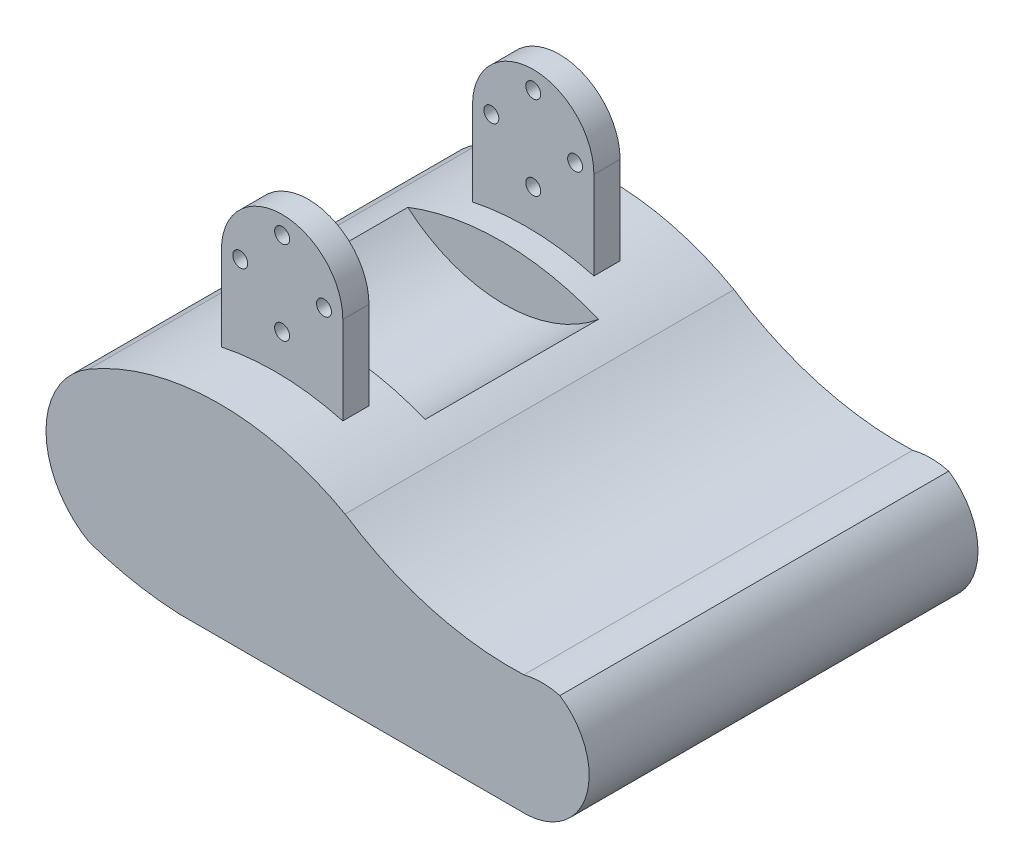
SolidWorks part; units mm, degrees
material "PLA"
ref_plane "Front Plane" through (0, 0, 0) normal (0, 0, 1) x (1, 0, 0)
ref_plane "Top Plane" through (0, 0, 0) normal (0, 1, 0) x (1, 0, 0)
ref_plane "Right Plane" through (0, 0, 0) normal (1, 0, 0) x (0, 0, -1)
sketch "Sketch1" plane through (0, 0, 0) normal (0, 0, 1) x (1, 0, 0)
  line L0 (-30, 0) -> (50, 0)
  line L1 (0, 0) -> (0, 25) construction
  line L2 (-30, 0) -> (-30, 25) construction
  line L3 (50, 0) -> (34.8329, 0) construction
  line L4 (-15, -2.8863) -> (48.734, -2.8863) construction
  line L5 (48.734, -2.8863) -> (48.734, 17.1137) construction
  line L6 (-15, -2.8863) -> (42.0254, -2.8863)
  line L7 (48.734, 17.1137) -> (42.7081, 17.1137) construction
  line L8 (-37.1668, 12.5) -> (-7.1668, 12.5) construction
  line L9 (-7.1668, 12.5) -> (12.8332, 12.5) construction
  line L10 (12.8332, 12.5) -> (12.8332, 25.4411) construction
  arc A0 (-30, 25) -> (-30, 0) centre (-22.6825, 12.5) ccw
  arc A7 (-30, 0) -> (-15, -2.8863) centre (-12.2067, 52.0503) ccw
  arc A8 (42.0254, -2.8863) -> (48.734, 17.1137) centre (42.7081, 8.0098) ccw
  arc A9 (48.734, 17.1137) -> (42.7081, 17.1137) centre (45.721, 5.4648) ccw
  arc A11 (-30, 25) -> (12.8332, 25.4411) centre (-8.1976, -12.2437) cw
  arc A12 (12.8332, 25.4411) -> (42.7081, 17.1137) centre (40.6286, 67.4056) ccw
  dimension "D5" = 20
  dimension "D6" = 30
  dimension "D1" = 30
  dimension "D2" = 50
  dimension "D3" = 25
  dimension "D4" = 25
  dimension "D7" = 20
extrude "Boss-Extrude1" add sketch "Sketch1" along normal blind 40
sketch "Sketch3" plane through (0, 0, 40) normal (0, 0, 1) x (1, 0, 0)
  line L0 (-17.1668, 44.0921) -> (-17.1668, 16.5921)
  line L1 (3.1204, 44.0921) -> (3.1204, 16.5921)
  line L2 (-17.1668, 16.5921) -> (3.1204, 16.5921)
  arc A0 (3.1204, 44.0921) -> (-17.1668, 44.0921) centre (-7.0232, 44.0921) ccw
  dimension "D1" = 27.5
  dimension "D2" = 27.5
extrude "Boss-Extrude2" add sketch "Sketch3" along normal blind 3.175 and the other way blind 1.2
ref_plane "Plane1" through (0, 0, 20) normal (0, 0, -1) x (-1, 0, 0)
ref_plane "Plane2" through (0, 0, 34.4) normal (0, 0, 1) x (1, 0, 0)
sketch "Sketch4" plane through (0, 0, 34.4) normal (0, 0, 1) x (1, 0, 0)
  arc A0 (-23.7828, 27.9998) -> (8.0976, 27.7176) centre (-7.6768, 46.5915) ccw
  arc A1 (-17.1668, 29.9699) -> (-30, 25) centre (-8.1976, -12.2437) ccw construction
  arc A2 (12.8332, 25.4411) -> (3.1204, 29.4017) centre (-8.1976, -12.2437) ccw construction
  arc A3 (-23.7828, 27.9998) -> (8.0976, 27.7176) centre (-8.1976, -12.2437) cw
extrude "Cut-Extrude2" cut sketch "Sketch4" against normal blind 29
sketch "Sketch10" plane through (0, 0, 43.175) normal (0, 0, 1) x (1, 0, 0)
  line L0 (-7.0232, 54.2357) -> (-7.0232, 44.2357) construction
  arc A0 (3.1204, 44.0921) -> (-17.1668, 44.0921) centre (-7.0232, 44.0921) ccw construction
  circle A1 centre (-7.0232, 44.2357) radius 7 construction
  circle A2 centre (-7.0232, 51.2357) radius 1.25
  circle A3 centre (-0.0232, 44.2357) radius 1.25
  circle A4 centre (-7.0232, 37.2357) radius 1.25
  circle A5 centre (-14.0232, 44.2357) radius 1.25
  dimension "D2" = 14
  dimension "D3" = 2.5
  dimension "D1" = 10
extrude "Cut-Extrude4" cut sketch "Sketch10" against normal blind 10
sketch "Sketch6" plane through (0, 0, 40) normal (0, 0, 1) x (1, 0, 0)
  line L4 (3.1204, 29.4017) -> (3.1204, 16.5921)
  line L6 (3.1204, 16.5921) -> (-17.1668, 16.5921)
  line L7 (-15, -2.8863) -> (42.0254, -2.8863)
  line L11 (-15, -2.8863) -> (42.0254, -2.8863)
  line L13 (-17.1668, 16.5921) -> (-17.1668, 29.9699)
  arc A0 (8.0976, 27.7176) -> (-23.7828, 27.9998) centre (-8.1976, -12.2437) ccw construction
  arc A1 (8.0976, 27.7176) -> (-23.7828, 27.9998) centre (-8.1976, -12.2437) ccw
  arc A7 (12.8332, 25.4411) -> (3.1204, 29.4017) centre (-8.1976, -12.2437) ccw
  arc A8 (-17.1668, 29.9699) -> (-30, 25) centre (-8.1976, -12.2437) ccw
  arc A9 (-30, 25) -> (-30, 0) centre (-22.6825, 12.5) ccw
  arc A10 (-30, 0) -> (-15, -2.8863) centre (-12.2067, 52.0503) ccw
  arc A11 (42.0254, -2.8863) -> (48.734, 17.1137) centre (42.7081, 8.0098) ccw
  arc A12 (48.734, 17.1137) -> (42.7081, 17.1137) centre (45.721, 5.4648) ccw
  arc A13 (12.8332, 25.4411) -> (42.7081, 17.1137) centre (40.6286, 67.4056) ccw
  arc A14 (12.8332, 25.4411) -> (3.1204, 29.4017) centre (-8.1976, -12.2437) ccw
  arc A15 (-17.1668, 29.9699) -> (-30, 25) centre (-8.1976, -12.2437) ccw
  arc A16 (-30, 25) -> (-30, 0) centre (-22.6825, 12.5) ccw
  arc A17 (-30, 0) -> (-15, -2.8863) centre (-12.2067, 52.0503) ccw
  arc A18 (42.0254, -2.8863) -> (48.734, 17.1137) centre (42.7081, 8.0098) ccw
  arc A19 (48.734, 17.1137) -> (42.7081, 17.1137) centre (45.721, 5.4648) ccw
  arc A20 (12.8332, 25.4411) -> (42.7081, 17.1137) centre (40.6286, 67.4056) ccw
  arc M12 (12.8332, 25.4411) -> (3.1204, 29.4017) centre (-8.1976, -12.2437) ccw
  arc M16 (-17.1668, 29.9699) -> (-30, 25) centre (-8.1976, -12.2437) ccw
  arc M17 (-30, 25) -> (-30, 0) centre (-22.6825, 12.5) ccw
  arc M18 (-30, 0) -> (-15, -2.8863) centre (-12.2067, 52.0503) ccw
  line M19 (-15, -2.8863) -> (42.0254, -2.8863)
  arc M20 (42.0254, -2.8863) -> (48.734, 17.1137) centre (42.7081, 8.0098) ccw
  arc M21 (48.734, 17.1137) -> (42.7081, 17.1137) centre (45.721, 5.4648) ccw
  arc M22 (42.7081, 17.1137) -> (12.8332, 25.4411) centre (40.6286, 67.4056) cw
  line M23 (3.1204, 29.4017) -> (3.1204, 16.5921)
  line M24 (3.1204, 16.5921) -> (-17.1668, 16.5921)
  line M25 (-17.1668, 16.5921) -> (-17.1668, 29.9699)
  dimension "D1" = 0
extrude "Boss-Extrude3" add sketch "Sketch6" along normal blind 12.5 contours M12 M23 M24 M25 M16 M17 M18 M19 M20 M21 M22 | A1 M23 M25 M24
mirror "Mirror4" about plane through (0, 0, 20) normal (0, 0, -1) of "Boss-Extrude3"
sketch "Sketch5" plane through (0, -2.8863, 0) normal (0, -1, 0) x (1, 0, 0)
  line L4 (39.0254, 49.5) -> (-12, 49.5)
  line L5 (39.0254, 49.5) -> (-12, 49.5)
  line L6 (-12, -9.5) -> (39.0254, -9.5)
  line L7 (-12, -9.5) -> (39.0254, -9.5)
  line L9 (39.0254, -9.5) -> (39.0254, 49.5)
  line L11 (-12, 49.5) -> (-12, -9.5)
  line L13 (39.0254, -9.5) -> (39.0254, 49.5)
  line L15 (-12, 49.5) -> (-12, -9.5)
  dimension "D1" = 3
extrude "Cut-Extrude3" cut sketch "Sketch5" against normal blind 3.175
mirror "Mirror5" about plane through (0, 0, 20) normal (0, 0, -1) of "Boss-Extrude2", "Cut-Extrude4"
